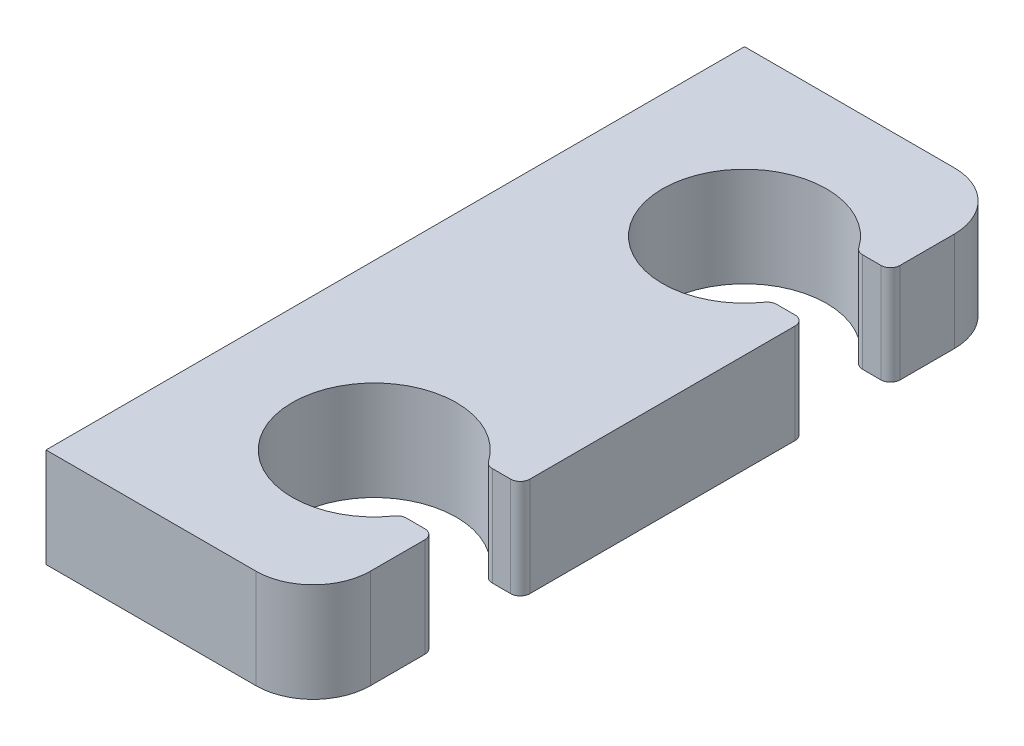
SolidWorks part; units mm, degrees
ref_plane "Alzado" through (0, 0, 0) normal (0, 0, 1) x (1, 0, 0)
ref_plane "Planta" through (0, 0, 0) normal (0, 1, 0) x (1, 0, 0)
ref_plane "Vista lateral" through (0, 0, 0) normal (1, 0, 0) x (0, 0, -1)
sketch "Croquis1" plane through (0, 0, 0) normal (0, 1, 0) x (1, 0, 0)
  line L1 (-3.5, -9.15) -> (3.5, -9.15)
  line L2 (-3.5, -9.15) -> (-3.5, 9.15)
  line L3 (-3.5, 9.15) -> (3.5, 9.15)
  line L4 (3.5, -9.15) -> (3.5, 9.15)
  line L5 (-3.5, -9.15) -> (3.5, 9.15) construction
  line L6 (-3.5, 9.15) -> (3.5, -9.15) construction
  point P0 (0, 0)
  dimension "D1" = 7
  dimension "D2" = 18.3
extrude "Saliente-Extruir1" add sketch "Croquis1" along normal blind 2.6
sketch "Croquis2" plane through (0, 2.6, 0) normal (0, 1, 0) x (1, 0, 0)
  line L0 (3.25, -3.725) -> (2.7671, -3.725) construction
  line L1 (3.25, -3.725) -> (2.7671, -3.725)
  line L2 (2.7671, -5.975) -> (3.25, -5.975) construction
  line L3 (2.7671, -5.975) -> (3.25, -5.975)
  line L4 (3.5, -9.15) -> (3.5, 9.15)
  line L5 (3.5, 9.15) -> (-3.5, 9.15)
  line L6 (-3.5, 9.15) -> (-3.5, -9.15)
  line L7 (-3.5, -9.15) -> (3.5, -9.15)
  line L8 (3.5, -9.15) -> (3.5, 9.15)
  line L9 (3.5, 9.15) -> (-3.5, 9.15)
  line L10 (-3.5, 9.15) -> (-3.5, -9.15)
  line L11 (-3.5, -9.15) -> (3.5, -9.15)
  line L12 (3.25, 5.975) -> (2.7671, 5.975) construction
  line L13 (3.25, 5.975) -> (2.7671, 5.975)
  line L14 (2.7671, 3.725) -> (3.25, 3.725) construction
  line L15 (2.7671, 3.725) -> (3.25, 3.725)
  line L20 (16.25, -85) -> (16.25, -19.1421)
  line L21 (19.1789, -12.0711) -> (33.3211, 2.0711)
  line L22 (36.25, 9.1421) -> (36.25, 195)
  line L23 (26.25, 205) -> (-73.75, 205)
  line L24 (-83.75, 195) -> (-83.75, 9.1421)
  line L25 (-80.8211, 2.0711) -> (-66.6789, -12.0711)
  line L26 (-63.75, -19.1421) -> (-63.75, -85)
  line L27 (-53.75, -95) -> (6.25, -95)
  line L28 (16.25, -85) -> (16.25, -19.1421)
  line L29 (19.1789, -12.0711) -> (33.3211, 2.0711)
  line L30 (36.25, 9.1421) -> (36.25, 195)
  line L31 (26.25, 205) -> (-73.75, 205)
  line L32 (-83.75, 195) -> (-83.75, 9.1421)
  line L33 (-80.8211, 2.0711) -> (-66.6789, -12.0711)
  line L34 (-63.75, -19.1421) -> (-63.75, -85)
  line L35 (-53.75, -95) -> (6.25, -95)
  arc A0 (2.5622, 6.0818) -> (2.5622, 3.6182) centre (0.8, 4.85) ccw construction
  arc A1 (2.5622, -3.6182) -> (2.5622, -6.0818) centre (0.8, -4.85) ccw construction
  arc A2 (2.5622, 6.0818) -> (2.5622, 3.6182) centre (0.8, 4.85) ccw
  arc A3 (2.5622, -3.6182) -> (2.5622, -6.0818) centre (0.8, -4.85) ccw
  arc A6 (3.25, -3.725) -> (3.5, -3.475) centre (3.25, -3.475) ccw construction
  arc A7 (2.5622, -3.6182) -> (2.7671, -3.725) centre (2.7671, -3.475) ccw construction
  arc A8 (3.25, -3.725) -> (3.5, -3.475) centre (3.25, -3.475) ccw
  arc A9 (2.5622, -3.6182) -> (2.7671, -3.725) centre (2.7671, -3.475) ccw
  arc A10 (2.7671, -5.975) -> (2.5622, -6.0818) centre (2.7671, -6.225) ccw construction
  arc A11 (3.5, -6.225) -> (3.25, -5.975) centre (3.25, -6.225) ccw construction
  arc A12 (2.7671, -5.975) -> (2.5622, -6.0818) centre (2.7671, -6.225) ccw
  arc A13 (3.5, -6.225) -> (3.25, -5.975) centre (3.25, -6.225) ccw
  arc A14 (3.25, 5.975) -> (3.5, 6.225) centre (3.25, 6.225) ccw construction
  arc A15 (2.5622, 6.0818) -> (2.7671, 5.975) centre (2.7671, 6.225) ccw construction
  arc A16 (3.25, 5.975) -> (3.5, 6.225) centre (3.25, 6.225) ccw
  arc A17 (2.5622, 6.0818) -> (2.7671, 5.975) centre (2.7671, 6.225) ccw
  arc A18 (2.7671, 3.725) -> (2.5622, 3.6182) centre (2.7671, 3.475) ccw construction
  arc A19 (3.5, 3.475) -> (3.25, 3.725) centre (3.25, 3.475) ccw construction
  arc A20 (3.5, 3.475) -> (3.25, 3.725) centre (3.25, 3.475) ccw
  arc A21 (2.7671, 3.725) -> (2.5622, 3.6182) centre (2.7671, 3.475) ccw
  arc A22 (6.25, -95) -> (16.25, -85) centre (6.25, -85) ccw
  arc A23 (19.1789, -12.0711) -> (16.25, -19.1421) centre (26.25, -19.1421) ccw
  arc A24 (33.3211, 2.0711) -> (36.25, 9.1421) centre (26.25, 9.1421) ccw
  arc A25 (36.25, 195) -> (26.25, 205) centre (26.25, 195) ccw
  arc A26 (-73.75, 205) -> (-83.75, 195) centre (-73.75, 195) ccw
  arc A27 (-83.75, 9.1421) -> (-80.8211, 2.0711) centre (-73.75, 9.1421) ccw
  arc A28 (-63.75, -19.1421) -> (-66.6789, -12.0711) centre (-73.75, -19.1421) ccw
  arc A29 (-63.75, -85) -> (-53.75, -95) centre (-53.75, -85) ccw
  arc A30 (6.25, -95) -> (16.25, -85) centre (6.25, -85) ccw
  arc A31 (19.1789, -12.0711) -> (16.25, -19.1421) centre (26.25, -19.1421) ccw
  arc A32 (33.3211, 2.0711) -> (36.25, 9.1421) centre (26.25, 9.1421) ccw
  arc A33 (36.25, 195) -> (26.25, 205) centre (26.25, 195) ccw
  arc A34 (-73.75, 205) -> (-83.75, 195) centre (-73.75, 195) ccw
  arc A35 (-83.75, 9.1421) -> (-80.8211, 2.0711) centre (-73.75, 9.1421) ccw
  arc A36 (-63.75, -19.1421) -> (-66.6789, -12.0711) centre (-73.75, -19.1421) ccw
  arc A37 (-63.75, -85) -> (-53.75, -95) centre (-53.75, -85) ccw
  line M7 (3.5, -9.15) -> (3.5, 9.15)
  dimension "D1" = 0
  dimension "D2" = 0
extrude "Cortar-Extruir2" cut sketch "Croquis2" against normal blind 10 contours A21 L15 A20 A16 L13 A17 A2 M7 | A13 L8 A8 L1 A9 A3 A12 L3
fillet "Redondeo1" radius 1.5 2 edges at (3.5, 1.3, -9.15) (3.5, 1.3, 9.15)
